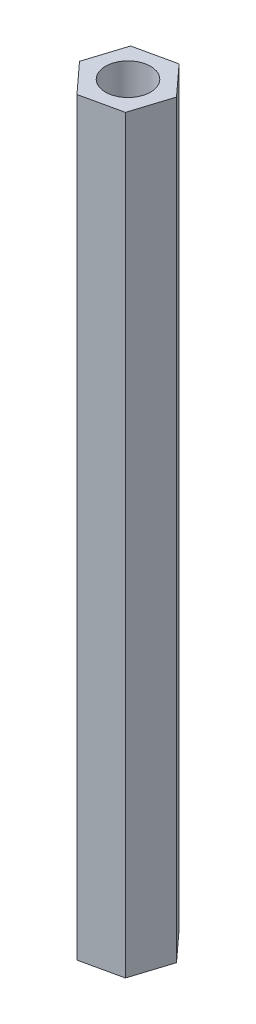
SolidWorks part; units mm, degrees
ref_plane "Front Plane" through (0, 0, 0) normal (0, 0, 1) x (1, 0, 0)
ref_plane "Top Plane" through (0, 0, 0) normal (0, 1, 0) x (1, 0, 0)
ref_plane "Right Plane" through (0, 0, 0) normal (1, 0, 0) x (0, 0, -1)
sketch "Sketch1" plane through (0, 0, 0) normal (0, 1, 0) x (1, 0, 0)
  line L1 (-1.8306, 2.0031) -> (-2.65, -0.5838)
  line L2 (-2.65, -0.5838) -> (-0.8194, -2.5869)
  line L3 (-0.8194, -2.5869) -> (1.8306, -2.0031)
  line L4 (1.8306, -2.0031) -> (2.65, 0.5838)
  line L5 (2.65, 0.5838) -> (0.8194, 2.5869)
  line L6 (0.8194, 2.5869) -> (-1.8306, 2.0031)
  circle A0 centre (0, 0) radius 2.35 construction
  circle A1 centre (0, 0) radius 1.5
  dimension "D3" = 3
  dimension "D1" = 5.3
  dimension "D2" = 4.7
extrude "Boss-Extrude1" add sketch "Sketch1" along normal blind 50
